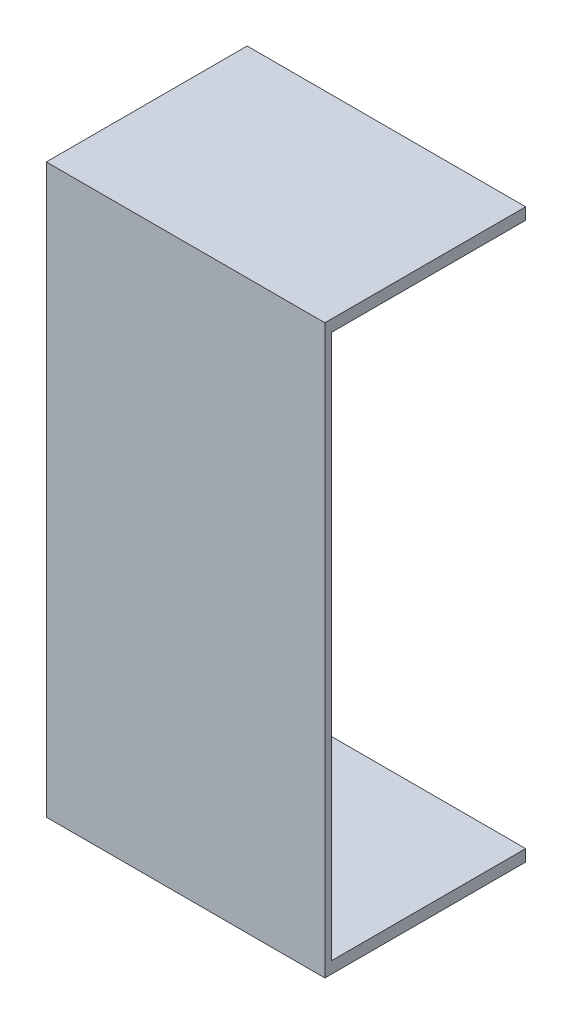
SolidWorks part; units mm, degrees
ref_plane "Front Plane" through (0, 0, 0) normal (0, 0, 1) x (1, 0, 0)
ref_plane "Top Plane" through (0, 0, 0) normal (0, 1, 0) x (1, 0, 0)
ref_plane "Right Plane" through (0, 0, 0) normal (1, 0, 0) x (0, 0, -1)
sketch "Sketch1" plane through (-174, 0, 0) normal (1, 0, 0) x (0, 0, -1)
  line L0 (-44, 88.8) -> (-13, 88.8) construction
  line L1 (-43, 87) -> (-13, 87) construction
  line L2 (-13, 87) -> (-13, 88.8) construction
  line L3 (-13, 1.2) -> (-13, 3) construction
  line L4 (-44, 1.2) -> (-13, 1.2) construction
  line L5 (-44, 1.2) -> (-44, 88.8) construction
  line L6 (-43, 87) -> (-43, 3) construction
  line L7 (-13, 3) -> (-43, 3) construction
  line L8 (-44, 88.8) -> (-13, 88.8)
  line L9 (-43, 87) -> (-13, 87)
  line L10 (-13, 87) -> (-13, 88.8)
  line L11 (-13, 1.2) -> (-13, 3)
  line L12 (-44, 1.2) -> (-13, 1.2)
  line L13 (-44, 1.2) -> (-44, 88.8)
  line L14 (-43, 87) -> (-43, 3)
  line L15 (-13, 3) -> (-43, 3)
extrude "Boss-Extrude1" add sketch "Sketch1" along normal up to surface (43 mm away)
